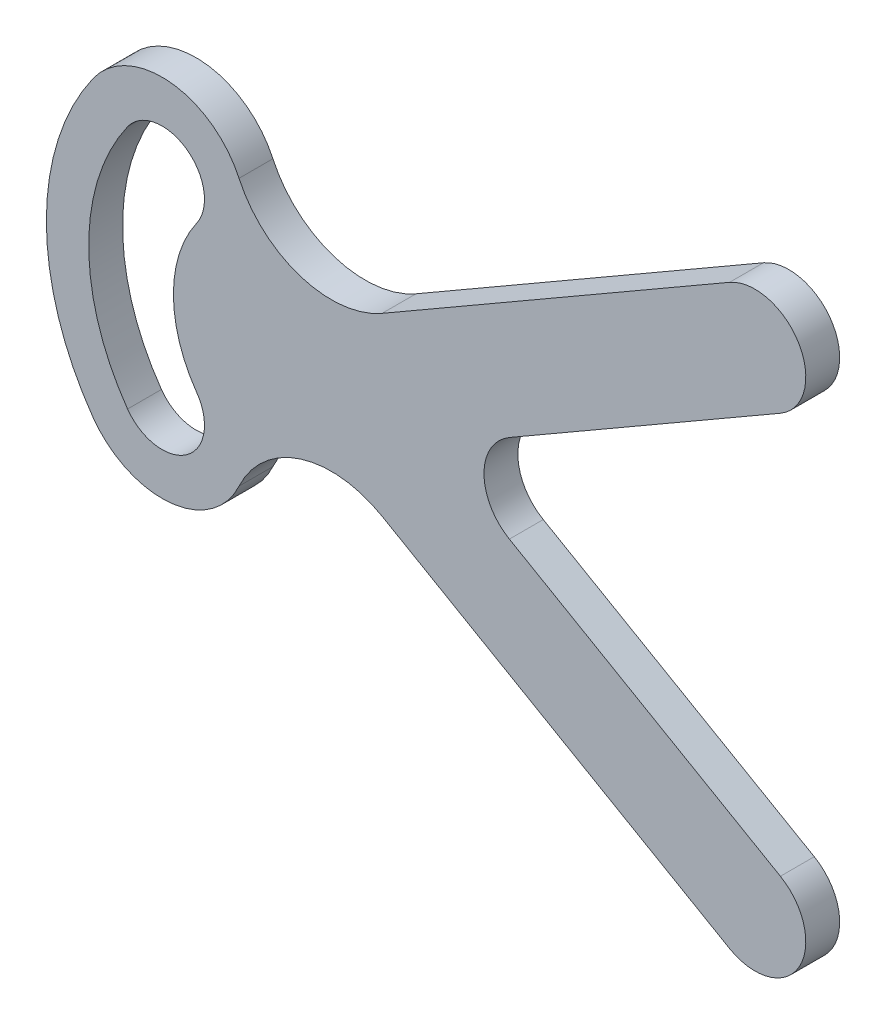
SolidWorks part; units mm, degrees
ref_plane "Alzado" through (0, 0, 0) normal (0, 0, 1) x (1, 0, 0)
ref_plane "Planta" through (0, 0, 0) normal (0, 1, 0) x (1, 0, 0)
ref_plane "Vista lateral" through (0, 0, 0) normal (1, 0, 0) x (0, 0, -1)
sketch "Croquis1" plane through (0, 0, 0) normal (0, 0, 1) x (1, 0, 0)
  line L0 (0, 0) -> (-72.3164, 0) construction
  line L1 (0, 0) -> (-50, 28.8675) construction
  line L2 (0, 0) -> (125, 72.1688) construction
  line L3 (117.5, 85.1592) -> (14.9342, 25.9428)
  line L4 (132.5, 59.1784) -> (52.5, 12.9904)
  line L5 (132.5, -59.1784) -> (52.5, -12.9904)
  line L6 (117.5, -85.1592) -> (14.9342, -25.9428)
  arc A0 (-50, 28.8675) -> (-50, -28.8675) centre (-9.1752, 0) ccw construction
  arc A1 (-70.4124, 43.3013) -> (-70.4124, -43.3013) centre (-9.1752, 0) ccw
  arc A3 (-27.3027, 39.3475) -> (-70.4124, 43.3013) centre (-50, 28.8675) ccw
  arc A5 (132.5, 59.1784) -> (117.5, 85.1592) centre (125, 72.1688) ccw
  arc A6 (14.9342, 25.9428) -> (-27.3027, 39.3475) centre (-0.0658, 51.9235) cw
  arc A7 (132.5, -59.1784) -> (117.5, -85.1592) centre (125, -72.1688) cw
  arc A8 (14.9342, -25.9428) -> (-27.3027, -39.3475) centre (-0.0658, -51.9235) ccw
  arc A9 (-27.3027, -39.3475) -> (-70.4124, -43.3013) centre (-50, -28.8675) cw
  arc A10 (-50, 28.8675) -> (-50, -28.8675) centre (-9.1752, 0) ccw construction
  arc A11 (-60.2062, 36.0844) -> (-60.2062, -36.0844) centre (-9.1752, 0) ccw
  arc A12 (-39.7938, 21.6506) -> (-39.7938, -21.6506) centre (-9.1752, 0) ccw
  arc A13 (-39.7938, 21.6506) -> (-60.2062, 36.0844) centre (-50, 28.8675) ccw
  arc A14 (-60.2062, -36.0844) -> (-39.7938, -21.6506) centre (-50, -28.8675) ccw
  arc A15 (52.5, 12.9904) -> (52.5, -12.9904) centre (60, 0) ccw
  point P7 (-72.3164, 0)
  point P23 (-59.1752, 0)
  point P30 (30, 0)
  dimension "D5" = 15
  dimension "D6" = 25
  dimension "D7" = 30
  dimension "D8" = 75
  dimension "D9" = 12.5
  dimension "D10" = 15
  dimension "D1" = 50
  dimension "D2" = 125
  dimension "D3" = 30
  dimension "D4" = 30
extrude "Saliente-Extruir2" add sketch "Croquis1" along normal blind 10
